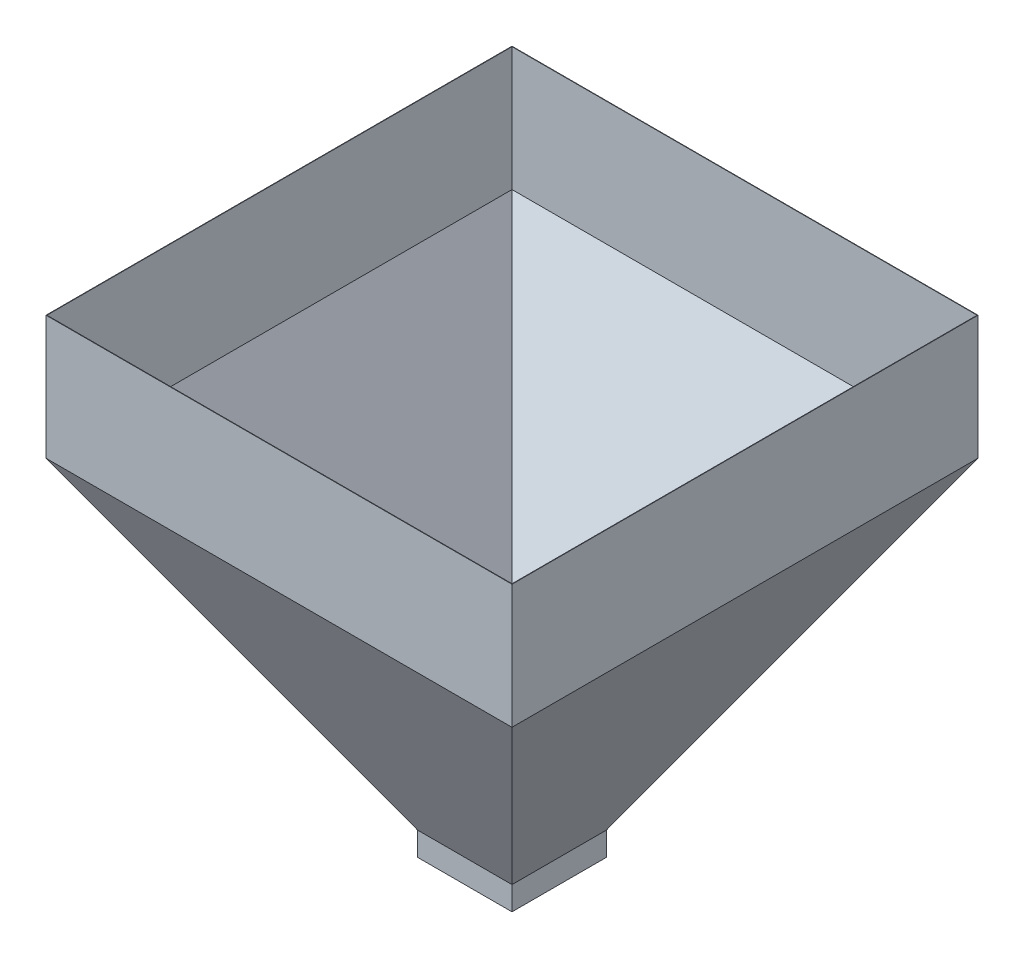
SolidWorks part; units mm, degrees
material "AISI 304"
ref_plane "Alzado" through (0, 0, 0) normal (0, 0, 1) x (1, 0, 0)
ref_plane "Planta" through (0, 0, 0) normal (0, 1, 0) x (1, 0, 0)
ref_plane "Vista lateral" through (0, 0, 0) normal (1, 0, 0) x (0, 0, -1)
sketch "Croquis1" plane through (0, 0, 0) normal (0, 1, 0) x (1, 0, 0)
  line L1 (-395, 395) -> (395, 395)
  line L2 (-395, 395) -> (-395, -395)
  line L3 (-395, -395) -> (395, -395)
  line L4 (395, 395) -> (395, -395)
  line L5 (-395, 395) -> (395, -395) construction
  line L6 (-395, -395) -> (395, 395) construction
  point P0 (0, 0)
  dimension "D1" = 790
ref_plane "Plano1" through (0, -546, 0) normal (0, 1, 0) x (1, 0, 0)
sketch "Croquis2" plane through (0, -546, 0) normal (0, 1, 0) x (1, 0, 0)
  line L0 (-395, 395) -> (395, -395) construction
  line L1 (-80, 80) -> (80, 80)
  line L2 (-80, 80) -> (-80, -80)
  line L3 (-80, -80) -> (80, -80)
  line L4 (80, 80) -> (80, -80)
  line L5 (-80, 80) -> (80, -80) construction
  line L6 (-80, -80) -> (80, 80) construction
  point P0 (0, 0)
  dimension "D1" = 160
loft "Recubrir1" add profiles "Croquis1", "Croquis2"
sketch "Croquis3" plane through (0, 0, 0) normal (0, 1, 0) x (1, 0, 0)
  line L1 (-395, 395) -> (395, 395)
  line L2 (-395, 395) -> (-395, -395)
  line L3 (-395, -395) -> (395, -395)
  line L4 (395, 395) -> (395, -395)
extrude "Saliente-Extruir1" add sketch "Croquis3" along normal blind 210
shell "Vaciado2" thickness 0.76
sketch "Croquis5" plane through (0, -546, 0) normal (0, -1, 0) x (1, 0, 0)
  line L1 (-80, 80) -> (80, 80)
  line L2 (-80, 80) -> (-80, -80)
  line L3 (-80, -80) -> (80, -80)
  line L4 (80, 80) -> (80, -80)
  line L5 (-80, 80) -> (80, -80) construction
  line L6 (-80, -80) -> (80, 80) construction
  line L7 (79.1226, -79.1226) -> (-79.1226, -79.1226)
  line L8 (79.1226, -79.1226) -> (79.1226, 79.1226)
  line L9 (79.1226, 79.1226) -> (-79.1226, 79.1226)
  line L10 (-79.1226, -79.1226) -> (-79.1226, 79.1226)
  line L11 (79.1226, -79.1226) -> (-79.1226, 79.1226) construction
  line L12 (79.1226, 79.1226) -> (-79.1226, -79.1226) construction
  point P4 (0, 0)
  point P11 (0, 0)
extrude "Saliente-Extruir2" add sketch "Croquis5" along normal blind 40
